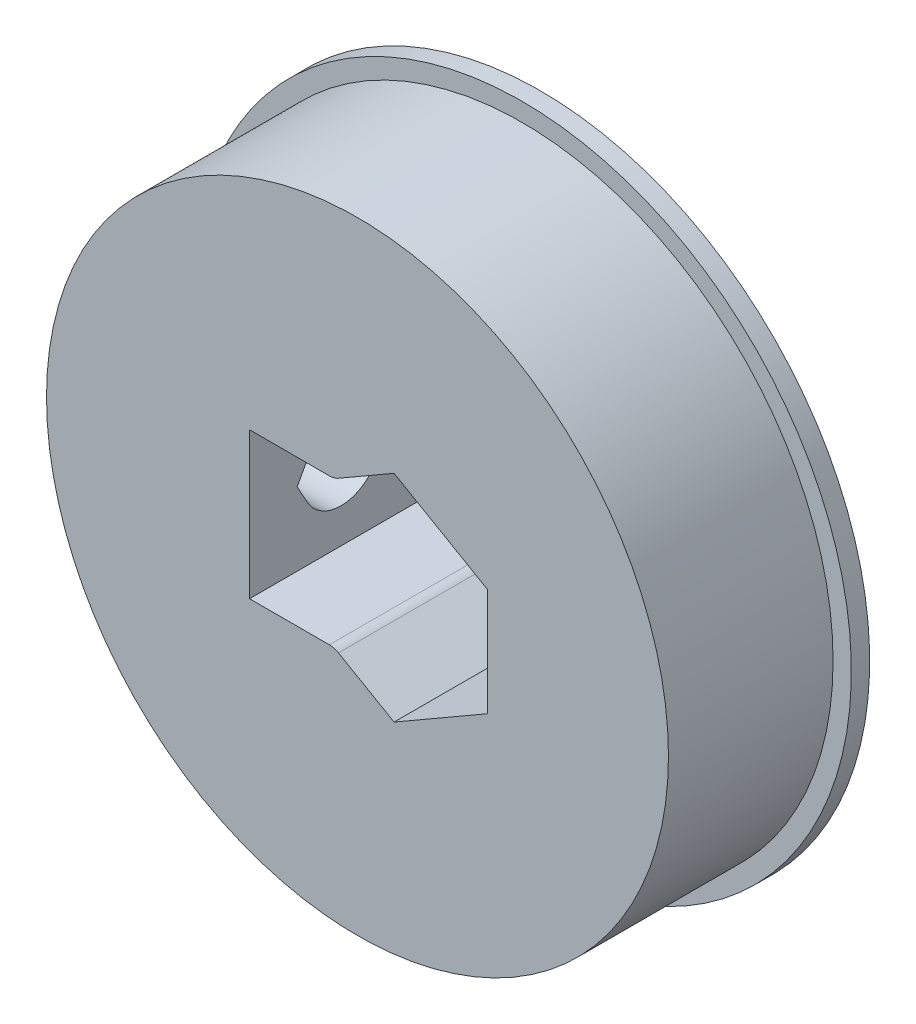
SolidWorks part; units mm, degrees
material "ABS"
ref_plane "Front Plane" through (0, 0, 0) normal (0, 0, 1) x (1, 0, 0)
ref_plane "Top Plane" through (0, 0, 0) normal (0, 1, 0) x (1, 0, 0)
ref_plane "Right Plane" through (0, 0, 0) normal (1, 0, 0) x (0, 0, -1)
sketch "Sketch1" plane through (0, 0, 0) normal (0, 0, 1) x (1, 0, 0)
  line L0 (0, 0) -> (-1, 0) construction
  line L1 (0, -2.9445) -> (2.55, -1.4722)
  line L2 (2.55, -1.4722) -> (2.55, 1.4722)
  line L3 (2.55, 1.4722) -> (0, 2.9445)
  line L4 (0, 2.9445) -> (-2.55, 1.4722)
  line L5 (-2.55, 1.4722) -> (-2.55, -1.4722)
  line L6 (-2.55, -1.4722) -> (0, -2.9445)
  circle A0 centre (0, 0) radius 2.55 construction
  circle A1 centre (-1, 0) radius 8.5
  dimension "D1" = 5.1
  dimension "D3" = 17
  dimension "D2" = 1
extrude "Boss-Extrude1" add sketch "Sketch1" along normal blind 5 contours A1
sketch "Sketch2" plane through (-2.55, 0, 0) normal (1, 0, 0) x (0, 0, -1)
  line L0 (0, 0) -> (-5, 0) construction
  line L1 (-0.1906, 0) -> (-1.3453, 2) construction
  line L2 (-1.3453, 2) -> (-3.6547, 2) construction
  line L3 (-3.6547, 2) -> (-4.8094, 0) construction
  line L4 (-4.8094, 0) -> (-3.6547, -2) construction
  line L5 (-3.6547, -2) -> (-1.3453, -2) construction
  line L6 (-1.3453, -2) -> (-0.1906, 0) construction
  line L7 (0, 1.4722) -> (0, -1.4722) construction
  line L8 (-5, 1.4722) -> (-5, -1.4722) construction
  line L10 (0, -2) -> (-5, -2)
  line L11 (0, -2) -> (0, 2)
  line L12 (0, 2) -> (-5, 2)
  line L13 (-5, -2) -> (-5, 2)
  line L14 (0, -2) -> (-5, 2) construction
  line L15 (0, 2) -> (-5, -2) construction
  circle A0 centre (-2.5, 0) radius 2 construction
  dimension "D1" = 4
extrude "M2 Hexnut Cutout" cut sketch "Sketch2" against normal blind 1.4 and the other way blind 1.4
fillet "Fillet1" radius 0.5 2 edges at (-1.6359, -2, 2.5) (-1.6359, 2, 2.5)
sketch "Sketch3" plane through (-3.95, 0, 0) normal (1, 0, 0) x (0, 0, -1)
  line L0 (0, 0) -> (-5, 0) construction
  line L1 (0, -2) -> (0, 2) construction
  line L2 (-5, 2) -> (-5, -2) construction
  line L3 (-2.5, 0) -> (-1.3, 0) construction
  line L4 (-1.3, 0) -> (-1.5813, 0.5083)
  line L5 (-1.3, 0) -> (-1.5813, -0.5083)
  line L6 (-1.3, 0) -> (-1.5813, -0.5083)
  line L7 (-1.3, 0) -> (-1.5813, 0.5083)
  line L8 (-2.5, 0) -> (-2.5, 1.4001) construction
  line L9 (-3.7, 0) -> (-3.4187, -0.5083)
  line L10 (-3.7, 0) -> (-3.4187, 0.5083)
  arc A0 (-1.5813, 0.5083) -> (-3.4187, 0.5083) centre (-2.5, 0) ccw
  arc A1 (-1.5813, 0.5083) -> (-3.4187, 0.5083) centre (-2.5, 0) ccw
  arc A2 (-3.4187, -0.5083) -> (-1.5813, -0.5083) centre (-2.5, 0) ccw
  arc A3 (-3.4187, -0.5083) -> (-1.5813, -0.5083) centre (-2.5, 0) ccw
  dimension "D1" = 1.2
  dimension "M2 Thru" = 2.1
extrude "M2 Thru" cut sketch "Sketch3" against normal through all contours L9 A2 L5 L4 A0 L10
sketch "Sketch4" plane through (0, 0, 0) normal (0, 0, -1) x (-1, 0, 0)
  circle A0 centre (1, 0) radius 8.5
  circle A1 centre (1, 0) radius 9
  circle A2 centre (1, 0) radius 8.5 construction
  dimension "D1" = 18
  dimension "D2" = 17
extrude "Boss-Extrude2" add sketch "Sketch4" against normal blind 0.5
equation "\"D1@Sketch4\"=\"D2@Sketch4\"+1"
